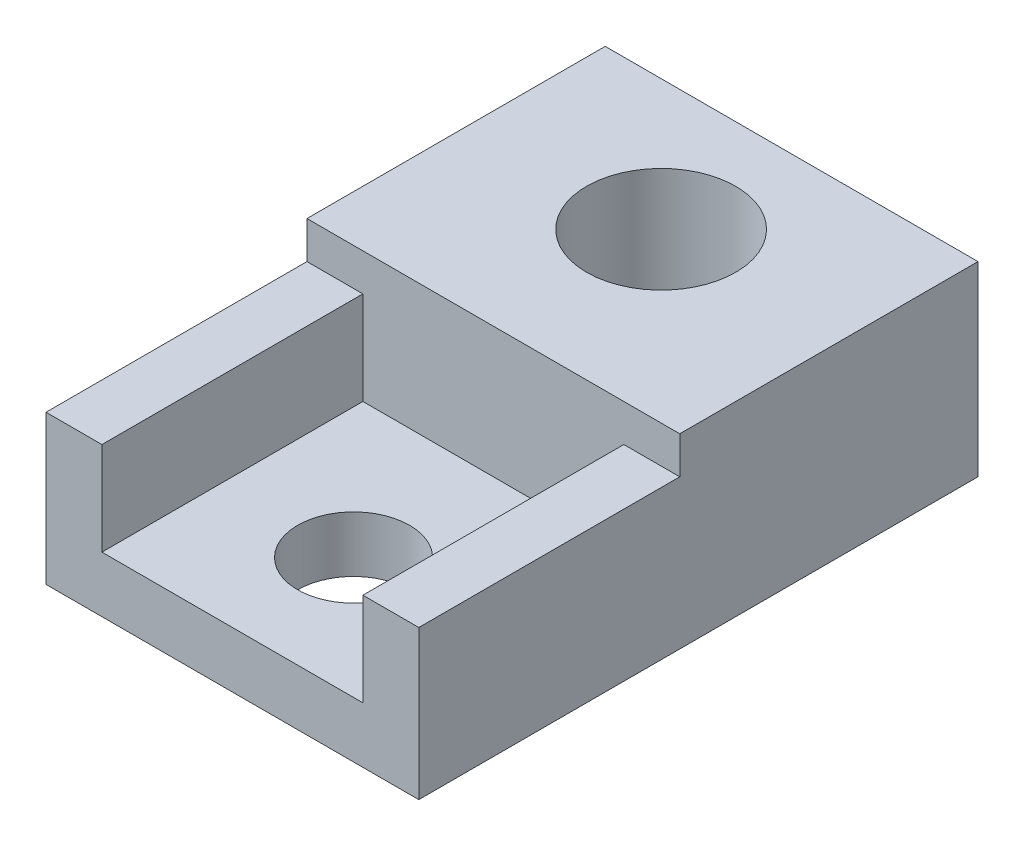
SolidWorks part; units mm, degrees
ref_plane "Front Plane" through (0, 0, 0) normal (0, 0, 1) x (1, 0, 0)
ref_plane "Top Plane" through (0, 0, 0) normal (0, 1, 0) x (1, 0, 0)
ref_plane "Right Plane" through (0, 0, 0) normal (1, 0, 0) x (0, 0, -1)
sketch "Sketch1" plane through (0, 0, 0) normal (0, 1, 0) x (1, 0, 0)
  line L1 (-10, -15) -> (10, -15)
  line L2 (-10, -15) -> (-10, 15)
  line L3 (-10, 15) -> (10, 15)
  line L4 (10, -15) -> (10, 15)
  line L5 (-10, -15) -> (10, 15) construction
  line L6 (-10, 15) -> (10, -15) construction
  point P0 (0, 0)
  dimension "D1" = 20
  dimension "D2" = 30
extrude "Boss-Extrude1" add sketch "Sketch1" along normal blind 3
sketch "Sketch2" plane through (0, 0, 0) normal (0, -1, 0) x (1, 0, 0)
  line L0 (10, -15) -> (-10, -15) construction
  line L1 (-2.5, -15) -> (2.5, -15)
  line L2 (-2.5, -15) -> (-2.5, -3)
  line L3 (-2.5, -3) -> (2.5, -3)
  line L4 (2.5, -15) -> (2.5, -3)
  line L5 (-2.5, -15) -> (2.5, -3) construction
  line L6 (-2.5, -3) -> (2.5, -15) construction
  point P0 (0, -9)
  dimension "D1" = 0
  dimension "D2" = 5
  dimension "D3" = 0
  dimension "D4" = 12
extrude "Boss-Extrude2" add sketch "Sketch2" along normal blind 3
sketch "Sketch3" plane through (0, 3, 0) normal (0, 1, 0) x (1, 0, 0)
  line L0 (10, 15) -> (-10, 15) construction
  circle A0 centre (0, 8) radius 4
  circle A1 centre (0, 8) radius 7
  dimension "D1" = 14
  dimension "D2" = 7
  dimension "D3" = 8
extrude "Boss-Extrude3" add sketch "Sketch3" along normal blind 7
sketch "Sketch4" plane through (0, 3, 0) normal (0, 1, 0) x (1, 0, 0)
  circle A1 centre (0, 8) radius 4
  circle A2 centre (0, 8) radius 4
  dimension "D1" = 0
extrude "Boss-Extrude4" add sketch "Sketch4" along normal blind 1
sketch "Sketch5" plane through (0, 3, 0) normal (0, 1, 0) x (1, 0, 0)
  line L0 (-10, -15) -> (10, -15) construction
  circle A0 centre (0, -8.5) radius 3
  dimension "D1" = 6
  dimension "D2" = 6.5
  dimension "D3" = 0
extrude "Cut-Extrude1" cut sketch "Sketch5" against normal through all both and the other way through all
chamfer "Chamfer1" [suppressed] distance 4 angle 45
sketch "Sketch6" plane through (0, 3, 0) normal (0, 1, 0) x (1, 0, 0)
  line L0 (10, -15) -> (10, 15) construction
  line L1 (-10, 15) -> (10, 15)
  line L2 (-10, 15) -> (-10, -1)
  line L3 (-10, -1) -> (10, -1)
  line L4 (10, 15) -> (10, -1)
  circle A0 centre (0, 8) radius 7 construction
  circle A1 centre (0, 8) radius 7
  circle A3 centre (0, 8) radius 4
  circle A4 centre (0, 8) radius 4
  line M6 (10, 15) -> (0, 15)
  circle M7 centre (0, 8) radius 7
  line M8 (0, 15) -> (-10, 15)
  line M9 (-10, 15) -> (-10, -15)
  line M11 (10, -15) -> (10, 15)
  dimension "D1" = 16
  dimension "D2" = 0
extrude "Boss-Extrude6" add sketch "Sketch6" along normal up to surface (7 mm away) contours A4 M7 | L3 M9 M11 M6 M7 M8 up to face at (0, 10, -1)
ref_plane "Plane1" through (0, 0, -8) normal (0, 0, 1) x (1, 0, 0)
ref_plane "Plane2" through (0, 0, 17) normal (0, 0, 1) x (1, 0, 0)
sketch "Sketch7" plane through (0, 0, 15) normal (0, 0, 1) x (1, 0, 0)
  line L4 (-10, 0) -> (10, 0)
  line L5 (10, 0) -> (10, 3)
  line L6 (10, 3) -> (-10, 3)
  line L7 (-10, 3) -> (-10, 0)
  line L8 (-10, 0) -> (10, 0)
  line L9 (10, 0) -> (10, 3)
  line L10 (10, 3) -> (-10, 3)
  line L11 (-10, 3) -> (-10, 0)
  dimension "D1" = 0
extrude "Boss-Extrude7" add sketch "Sketch7" along normal blind 19
mirror "Mirror3" about plane through (0, 0, 17) normal (0, 0, 1) of "Boss-Extrude6", "Boss-Extrude4", "Boss-Extrude3", "Boss-Extrude2", "Boss-Extrude1"
sketch "Sketch8" plane through (0, 0, 37) normal (0, 0, -1) x (-1, 0, 0)
  line L4 (2.5, 0) -> (-2.5, 0)
  line L5 (-2.5, 0) -> (-2.5, -3)
  line L6 (-2.5, -3) -> (2.5, -3)
  line L7 (2.5, -3) -> (2.5, 0)
  line L8 (2.5, 0) -> (-2.5, 0)
  line L9 (-2.5, 0) -> (-2.5, -3)
  line L10 (-2.5, -3) -> (2.5, -3)
  line L11 (2.5, -3) -> (2.5, 0)
  dimension "D1" = 0
extrude "Boss-Extrude8" add sketch "Sketch8" along normal blind 12
sketch "Sketch10" plane through (0, 4, 0) normal (0, 1, 0) x (1, 0, 0)
  circle A0 centre (0, 8) radius 4 construction
  circle A1 centre (0, -42) radius 4 construction
  circle A2 centre (0, 8) radius 4
  circle A3 centre (0, -42) radius 4
extrude "Cut-Extrude2" cut sketch "Sketch10" against normal blind 1.5
sketch "Sketch12" plane through (0, 3, 0) normal (0, 1, 0) x (1, 0, 0)
  line L1 (10, -33) -> (7, -33)
  line L2 (10, -33) -> (10, -1)
  line L3 (10, -1) -> (7, -1)
  line L4 (-10, -1) -> (-10, -33)
  line L5 (-10, -33) -> (10, -33)
  line L6 (10, -33) -> (10, -1)
  line L7 (10, -1) -> (-10, -1)
  line L8 (-10, -1) -> (-10, -33)
  line L9 (-10, -33) -> (10, -33)
  line L10 (10, -33) -> (10, -1)
  line L11 (10, -1) -> (-10, -1)
  line L12 (7, -33) -> (7, -1)
  line L13 (-10, -33) -> (-7, -33)
  line L14 (-10, -33) -> (-10, -1)
  line L15 (-10, -1) -> (-7, -1)
  line L16 (-7, -33) -> (-7, -1)
  line M11 (-10, -1) -> (-10, -33)
  line M12 (-10, -33) -> (10, -33)
  line M13 (10, -33) -> (10, -1)
  line M14 (10, -1) -> (-10, -1)
  dimension "D2" = 3
  dimension "D3" = 3
  dimension "D1" = 0
extrude "Boss-Extrude9" add sketch "Sketch12" along normal blind 5 contours L12 M12 M13 M14 | L16 L11 M12 M11
sketch "Sketch13" plane through (0, 0, 0) normal (0, 1, 0) x (1, 0, 0)
  line L0 (-7.15, -17) -> (7.15, -17) construction
  line L1 (-22.3376, -17) -> (21.6805, -17)
  line L2 (-22.3376, -17) -> (-22.3376, -58.9828)
  line L3 (-22.3376, -58.9828) -> (21.6805, -58.9828)
  line L4 (21.6805, -17) -> (21.6805, -58.9828)
  dimension "D1" = 0
extrude "Cut-Extrude3" cut sketch "Sketch13" against normal through all both and the other way through all
sketch "Sketch14" plane through (0, 0, 17) normal (0, 0, 1) x (1, 0, 0)
  line L8 (10, 8) -> (7, 8)
  line L9 (7, 8) -> (7, 3)
  line L10 (7, 3) -> (-7, 3)
  line L11 (-7, 3) -> (-7, 8)
  line L12 (-7, 8) -> (-10, 8)
  line L13 (-10, 8) -> (-10, 0)
  line L14 (-10, 0) -> (10, 0)
  line L15 (10, 0) -> (10, 8)
  line L16 (10, 8) -> (7, 8)
  line L17 (7, 8) -> (7, 3)
  line L18 (7, 3) -> (-7, 3)
  line L19 (-7, 3) -> (-7, 8)
  line L20 (-7, 8) -> (-10, 8)
  line L21 (-10, 8) -> (-10, 0)
  line L22 (-10, 0) -> (10, 0)
  line L23 (10, 0) -> (10, 8)
  dimension "D1" = 0
extrude "Cut-Extrude4" cut sketch "Sketch14" against normal blind 2
